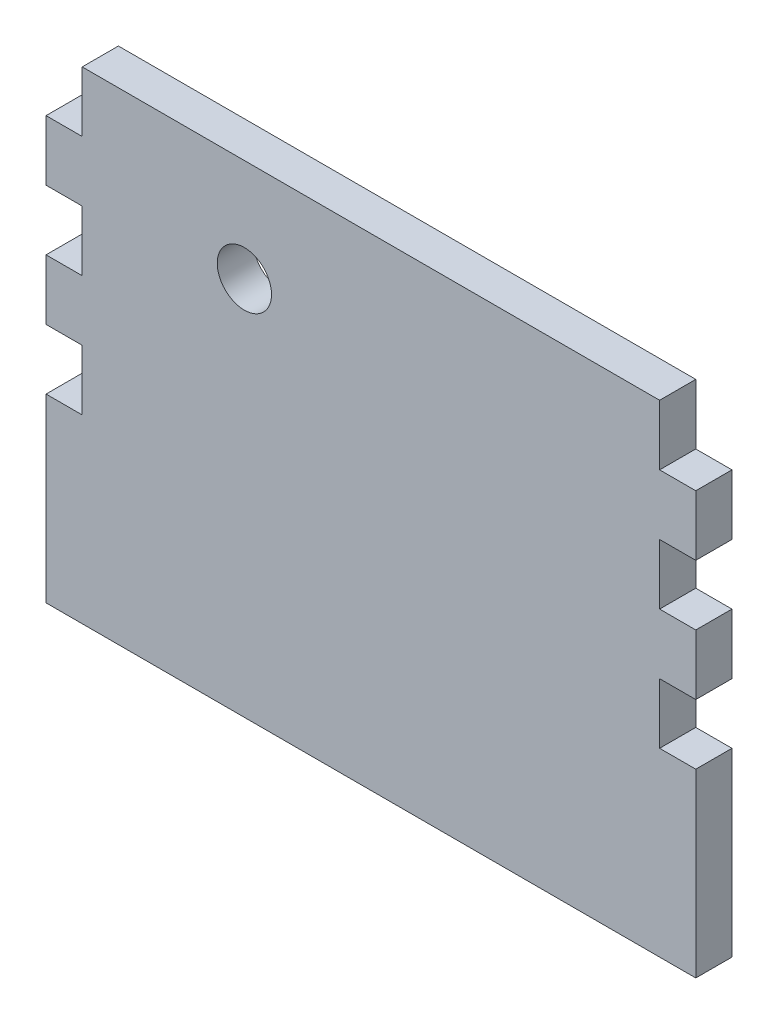
SolidWorks part; units mm, degrees
ref_plane "Front Plane" through (0, 0, 0) normal (0, 0, 1) x (1, 0, 0)
ref_plane "Top Plane" through (0, 0, 0) normal (0, 1, 0) x (1, 0, 0)
ref_plane "Right Plane" through (0, 0, 0) normal (1, 0, 0) x (0, 0, -1)
sketch "Sketch1" plane through (0, 0, 0) normal (0, 0, 1) x (1, 0, 0)
  line L1 (-26.945, 20) -> (26.945, 20)
  line L2 (-26.945, 20) -> (-26.945, -20)
  line L3 (-26.945, -20) -> (26.945, -20)
  line L4 (26.945, 20) -> (26.945, -20)
  line L5 (-26.945, 20) -> (26.945, -20) construction
  line L6 (-26.945, -20) -> (26.945, 20) construction
  point P0 (0, 0)
  dimension "D1" = 53.89
  dimension "D2" = 40
extrude "Boss-Extrude1" add sketch "Sketch1" along normal blind 3 contours L2 L3 L4 L1
sketch "Sketch2" plane through (0, 0, 3) normal (0, 0, 1) x (1, 0, 0)
  line L0 (0, -1.65) -> (0, 1.65) construction
  line L1 (-26.945, 20) -> (-23.945, 20)
  line L2 (-26.945, 20) -> (-26.945, 15)
  line L3 (-26.945, 15) -> (-23.945, 15)
  line L4 (-23.945, 20) -> (-23.945, 15)
  line L5 (-26.945, 5) -> (-23.945, 5)
  line L6 (-26.945, 5) -> (-26.945, 10)
  line L7 (-26.945, 10) -> (-23.945, 10)
  line L8 (-23.945, 5) -> (-23.945, 10)
  line L9 (26.945, 15) -> (23.945, 15)
  line L10 (23.945, 20) -> (23.945, 15)
  line L11 (26.945, 20) -> (23.945, 20)
  line L12 (26.945, 20) -> (26.945, 15)
  line L13 (26.945, 10) -> (23.945, 10)
  line L14 (23.945, 5) -> (23.945, 10)
  line L15 (26.945, 5) -> (23.945, 5)
  line L16 (26.945, 5) -> (26.945, 10)
  line L17 (-26.945, 20) -> (-26.945, -20) construction
  line L18 (-26.945, -20) -> (26.945, -20) construction
  line L19 (26.945, -5) -> (23.945, -5)
  line L20 (-26.945, 0) -> (-23.945, 0)
  line L21 (-26.945, 0) -> (-26.945, -5)
  line L22 (-26.945, -5) -> (-23.945, -5)
  line L23 (-23.945, 0) -> (-23.945, -5)
  line L24 (23.945, 0) -> (23.945, -5)
  line L25 (26.945, 0) -> (23.945, 0)
  line L26 (26.945, 0) -> (26.945, -5)
  circle A0 centre (-10.495, 11.5) radius 2.25
  dimension "D5" = 4.5
  dimension "D1" = 3
  dimension "D2" = 5
  dimension "D3" = 5
  dimension "D4" = 3
  dimension "D6" = 5
  dimension "D7" = 31.5
  dimension "D8" = 16.45
  dimension "D9" = 3
  dimension "D10" = 5
  dimension "D11" = 5
extrude "Cut-Extrude1" cut sketch "Sketch2" against normal blind 3
equation "\"D1@Sketch1\"=47.89 + 6"
equation "\"D3@Sketch2\"=\"D2@Sketch2\""
equation "\"D4@Sketch2\"=\"D1@Sketch2\""
equation "\"D8@Sketch2\"=13.95+\"D1@Sketch2\" - 0.5"
equation "\"D9@Sketch2\"=\"D1@Sketch2\""
equation "\"D10@Sketch2\"=\"D2@Sketch2\""
equation "\"D11@Sketch2\"=\"D6@Sketch2\""
equation "\"D7@Sketch2\"=32.50 - 1"
